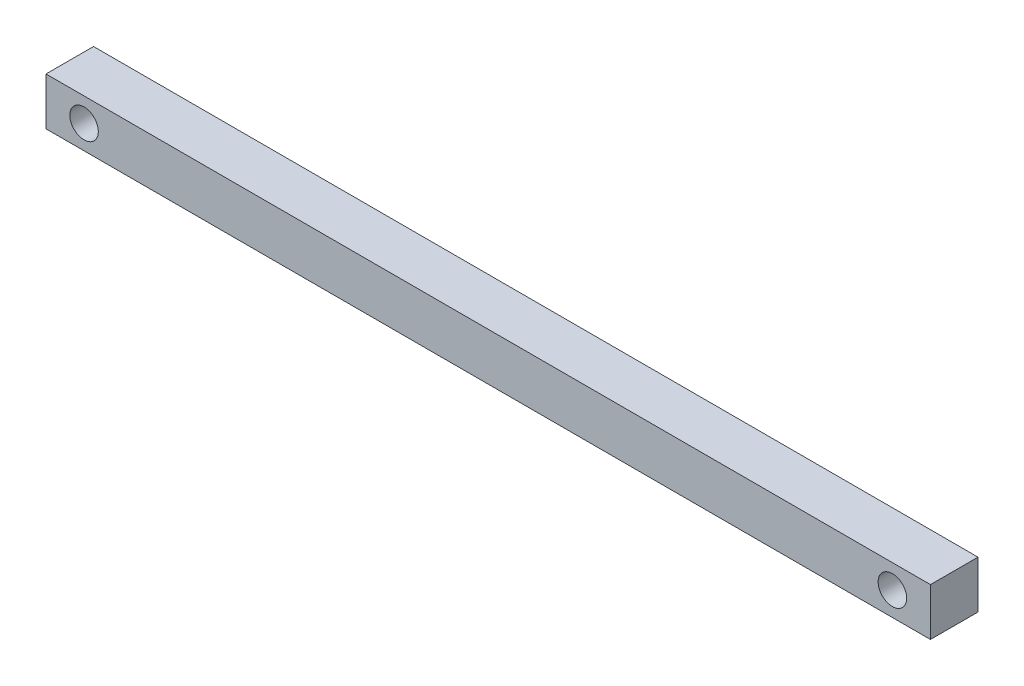
SolidWorks part; units mm, degrees
ref_plane "Front Plane" through (0, 0, 0) normal (0, 0, 1) x (1, 0, 0)
ref_plane "Top Plane" through (0, 0, 0) normal (0, 1, 0) x (1, 0, 0)
ref_plane "Right Plane" through (0, 0, 0) normal (1, 0, 0) x (0, 0, -1)
sketch "Sketch1" plane through (0, 0, 0) normal (0, 0, 1) x (1, 0, 0)
  line L0 (-434.7616, 0) -> (403.8512, 0) construction
  line L1 (0, 230.4841) -> (0, -272.146) construction
  line L3 (-232.5, 12.5) -> (232.5, 12.5)
  line L4 (-232.5, 12.5) -> (-232.5, -12.5)
  line L5 (-232.5, -12.5) -> (232.5, -12.5)
  line L6 (232.5, 12.5) -> (232.5, -12.5)
  circle A0 centre (-212.5, 0) radius 7.5
  circle A1 centre (212.5, 0) radius 7.5
  point P5 (0, 0)
  dimension "D3" = 15
  dimension "D4" = 15
  dimension "D1" = 465
  dimension "D2" = 25
  dimension "D5" = 212.5
  dimension "D6" = 212.5
extrude "Boss-Extrude1" add sketch "Sketch1" along normal blind 25
